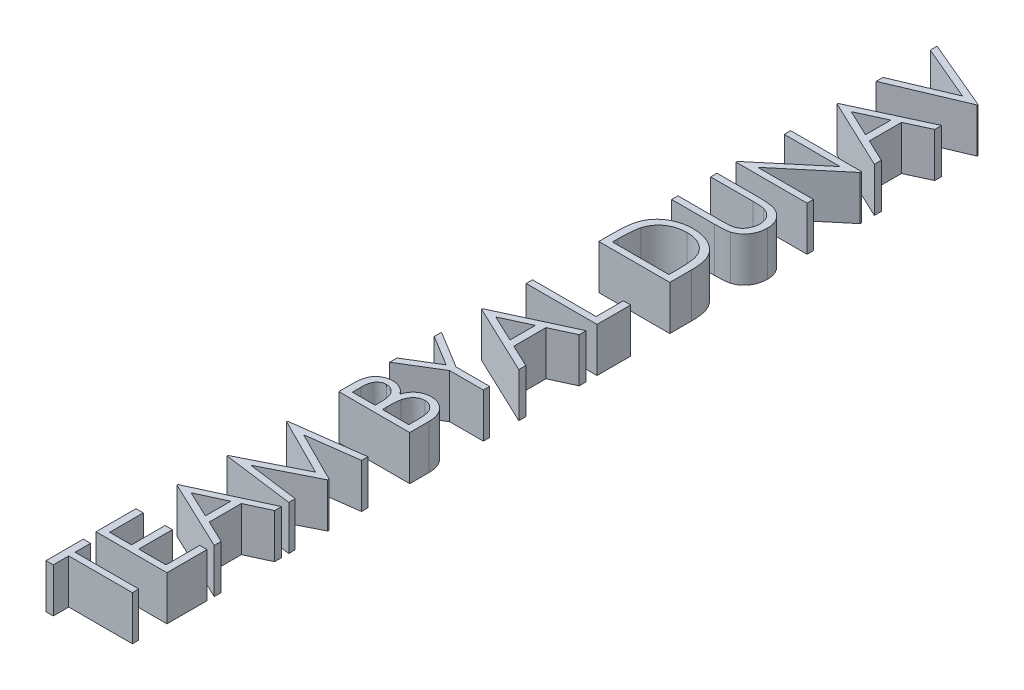
SolidWorks part; units mm, degrees
ref_plane "Front Plane" through (0, 0, 0) normal (0, 0, 1) x (1, 0, 0)
ref_plane "Top Plane" through (0, 0, 0) normal (0, 1, 0) x (1, 0, 0)
ref_plane "Right Plane" through (0, 0, 0) normal (1, 0, 0) x (0, 0, -1)
sketch "Sketch2" plane through (0, 0, 0) normal (0, 1, 0) x (1, 0, 0)
  line L0 (-53.9415, 53.4839) -> (-53.9415, -66.4572) construction
  text T0 "TEAM BYAL DUNAV" font "Century Gothic" height 8
extrude "Boss-Extrude2" add sketch "Sketch2" along normal blind 5
